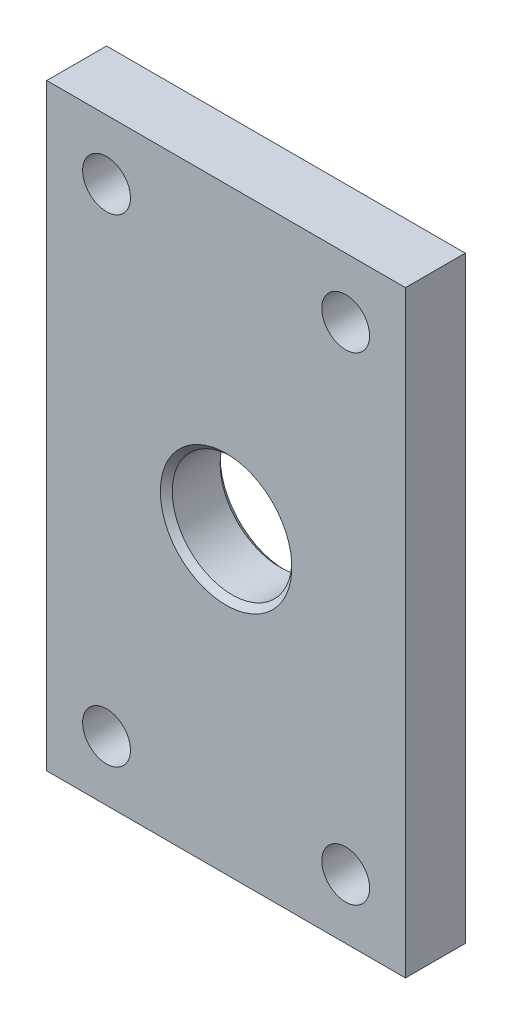
SolidWorks part; units mm, degrees
ref_plane "Front Plane" through (0, 0, 0) normal (1, 0, 0) x (0, 1, 0)
ref_plane "Top Plane" through (0, 0, 0) normal (0, 0, 1) x (0, 1, 0)
ref_plane "Right Plane" through (0, 0, 0) normal (0, 1, 0) x (-1, 0, 0)
sketch "Sketch1" plane through (0, 0, 0) normal (0, 0, 1) x (0, 1, 0)
  line L1 (-50, -30) -> (50, -30)
  line L2 (-50, -30) -> (-50, 30)
  line L3 (-50, 30) -> (50, 30)
  line L4 (50, -30) -> (50, 30)
  line L5 (-50, -30) -> (50, 30) construction
  line L6 (-50, 30) -> (50, -30) construction
  point P0 (0, 0)
extrude "Boss-Extrude1" add sketch "Sketch1" along normal mid plane 10
sketch "Sketch2" plane through (0, 0, 0) normal (0, 0, 1) x (0, 1, 0)
  circle A0 centre (-40, -20) radius 4
  circle A1 centre (40, -20) radius 4
  circle A2 centre (-40, 20) radius 4
  circle A3 centre (40, 20) radius 4
extrude "Cut-Extrude2" cut sketch "Sketch2" against normal through all from offset 5
sketch "Sketch3" plane through (0, 0, 0) normal (0, 0, 1) x (0, 1, 0)
  circle A0 centre (0, 0) radius 10
extrude "Cut-Extrude4" cut sketch "Sketch3" against normal through all from offset 5
chamfer "Chamfer1" distance 1 angle 45 2 edges at (10, 0, -5) (10, 0, 5)
